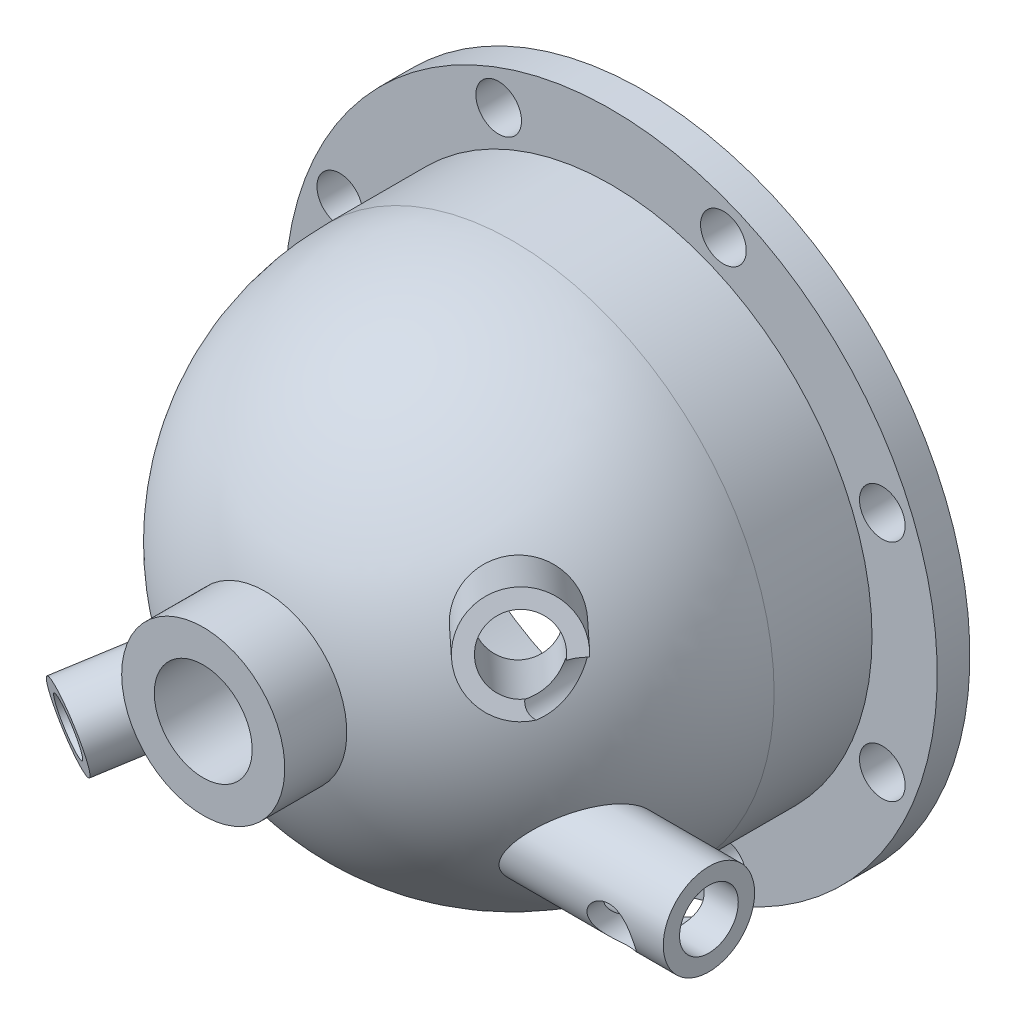
SolidWorks part; units mm, degrees
ref_plane "前视基准面" through (0, 0, 0) normal (0, 0, 1) x (1, 0, 0)
ref_plane "上视基准面" through (0, 0, 0) normal (0, 1, 0) x (1, 0, 0)
ref_plane "右视基准面" through (0, 0, 0) normal (1, 0, 0) x (0, 0, -1)
sketch "草图1" plane through (0, 0, 0) normal (0, 1, 0) x (1, 0, 0)
  line L0 (0, 0) -> (0, -100) construction
  line L1 (0, 40) -> (100, 40)
  line L2 (100, 40) -> (100, 30)
  line L3 (100, 30) -> (80, 30)
  line L4 (80, 30) -> (80, 0)
  line L5 (25, -75.99) -> (25, -95)
  line L6 (25, -95) -> (0, -95)
  line L7 (0, -95) -> (0, 40)
  arc A0 (80, 0) -> (25, -75.99) centre (0.5522, -0.3962) cw
revolve "旋转1" add sketch "草图1" angle 360 about L0
sketch3d "3D草图1"
  line L0 (0, 0, 0) -> (72.9755, 42.1324, 70.7066)
sweep "扫描2" add path "3D草图1" circular profile diameter 30 parameters "D3"=30
sketch3d "3D草图2"
  line L0 (0, 0, 0) -> (-45.4663, -26.25, 90.9327)
sweep "扫描4" add path "3D草图2" circular profile diameter 24 parameters "D3"=24
sketch3d "3D草图4"
  line L0 (-40, -30, 40) -> (100, -30, 40)
sweep "扫描8" add path "3D草图4" circular profile diameter 28 parameters "D3"=28
sketch "草图9" plane through (0, 0, 0) normal (0, 1, 0) x (1, 0, 0)
  line L0 (0, 0) -> (0, -100) construction
  line L1 (0, 40) -> (72, 40)
  line L2 (72, 40) -> (72, 0)
  line L3 (0, -72) -> (0, 40)
  arc A0 (72, 0) -> (0, -72) centre (-0.0058, 0.0058) cw
revolve "切除-旋转1" cut sketch "草图9" angle 360 about L0
sketch3d "3D草图5"
  line L0 (0, 0, 0) -> (74.3024, 42.8985, 71.9922)
sweep "切除-扫描2" cut path "3D草图5" circular profile diameter 20 parameters "D3"=20
sketch3d "3D草图6"
  line L0 (0, 0, 0) -> (-46.3324, -26.75, 92.6647)
sweep "切除-扫描4" cut path "3D草图6" circular profile diameter 16 parameters "D3"=16
sketch3d "3D草图7"
  line L0 (-40, -30, 40) -> (102, -30, 40)
sweep "切除-扫描6" cut path "3D草图7" circular profile diameter 18 parameters "D3"=18
sketch3d "3D草图8"
  line L0 (0, 0, 0) -> (0, 0, 97)
sweep "切除-扫描8" cut path "3D草图8" circular profile diameter 30 parameters "D3"=30
ref_plane "基准面1" through (0, 0, -40) normal (0, 0, 1) x (1, 0, 0)
sketch "草图14" plane through (0, 0, -40) normal (0, 0, 1) x (1, 0, 0)
  circle A0 centre (83.1492, 34.4415) radius 7
  circle A1 centre (34.4415, 83.1492) radius 7
  circle A2 centre (-34.4415, 83.1492) radius 7
  circle A3 centre (-83.1492, 34.4415) radius 7
  circle A4 centre (-83.1492, -34.4415) radius 7
  circle A5 centre (-34.4415, -83.1492) radius 7
  circle A6 centre (34.4415, -83.1492) radius 7
  circle A7 centre (83.1492, -34.4415) radius 7
extrude "切除-拉伸1" cut sketch "草图14" along normal through all
